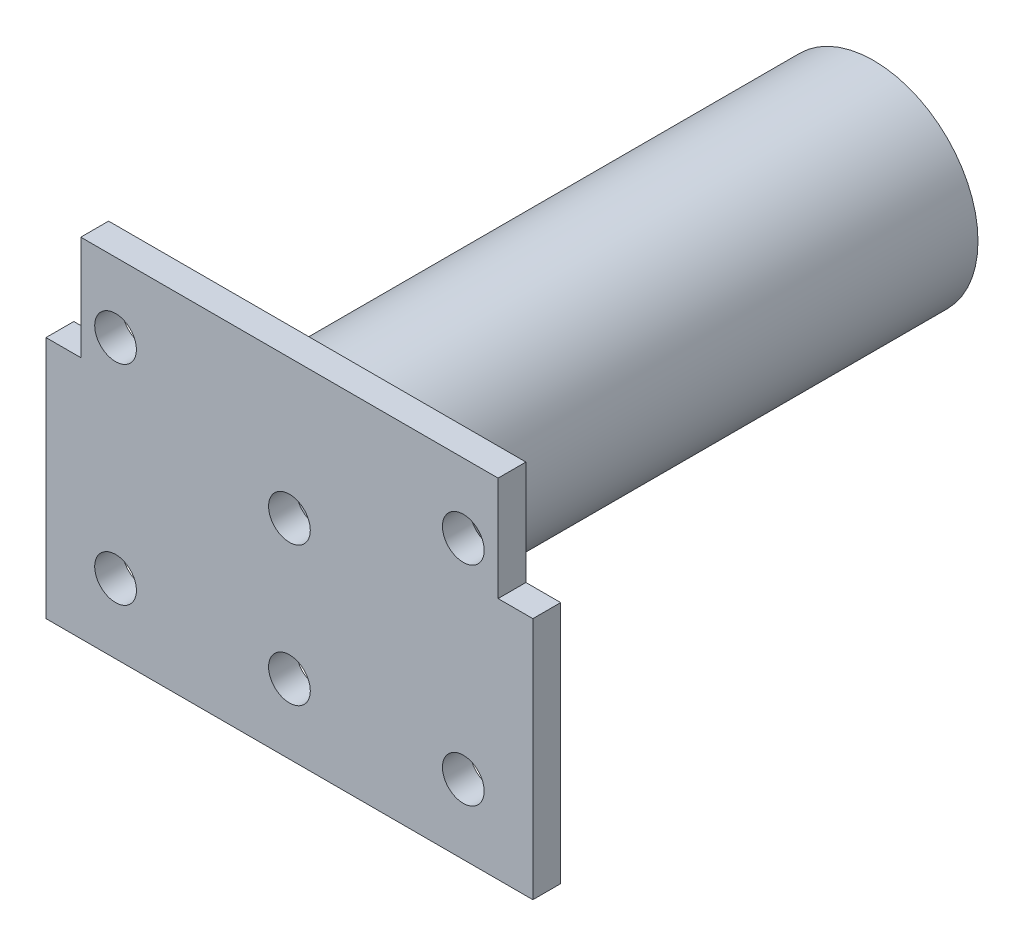
SolidWorks part; units mm, degrees
ref_plane "Alzado" through (0, 0, 0) normal (0, 0, 1) x (1, 0, 0)
ref_plane "Planta" through (0, 0, 0) normal (0, 1, 0) x (1, 0, 0)
ref_plane "Vista lateral" through (0, 0, 0) normal (1, 0, 0) x (0, 0, -1)
sketch "Croquis1" plane through (0, 0, 0) normal (0, 0, 1) x (1, 0, 0)
  line L1 (-35, -15) -> (35, -15)
  line L2 (-35, -15) -> (-35, 15)
  line L3 (-35, 15) -> (35, 15)
  line L4 (35, -15) -> (35, 15)
  circle A3 centre (0, -5) radius 3
  circle A4 centre (25, -5) radius 3
  circle A5 centre (-25, -5) radius 3
  point P0 (0, 0)
  dimension "D3" = 6
  dimension "D4" = 6
  dimension "D5" = 6
  dimension "D7" = 10
  dimension "D6" = 10
  dimension "D8" = 35
  dimension "D1" = 30
  dimension "D2" = 70
extrude "Saliente-Extruir1" add sketch "Croquis1" along normal blind 4
sketch "Croquis3" plane through (0, 0, 0) normal (0, 0, 1) x (1, 0, 0)
  line L0 (35, 15) -> (35, 35)
  line L1 (35, 35) -> (-35, 35)
  line L2 (-35, 35) -> (-35, 15)
  line L3 (35, 15) -> (-35, 15)
  dimension "D1" = 20
extrude "Saliente-Extruir2" add sketch "Croquis3" along normal blind 4
sketch "Croquis4" plane through (0, 0, 0) normal (0, 0, -1) x (-1, 0, 0)
  line L0 (-35, -15) -> (-35, 35) construction
  line L1 (-35, 35) -> (35, 35) construction
  circle A0 centre (0, 15) radius 15
  dimension "D1" = 30
  dimension "D2" = 35
  dimension "D3" = 20
extrude "Saliente-Extruir3" add sketch "Croquis4" along normal blind 80
sketch "Croquis5" plane through (0, 0, 0) normal (0, 0, -1) x (-1, 0, 0)
  line L0 (-35, -15) -> (-35, 35) construction
  line L1 (-35, 35) -> (35, 35) construction
  line L2 (35, 35) -> (35, -15) construction
  circle A0 centre (-25, 25) radius 3
  circle A1 centre (25, 25) radius 3
  dimension "D1" = 6
  dimension "D2" = 6
  dimension "D4" = 10
  dimension "D5" = 10
  dimension "D6" = 10
  dimension "D3" = 10
extrude "Cortar-Extruir1" cut sketch "Croquis5" against normal up to surface (4 mm away) up to face at (0, 10, 4)
sketch "Croquis6" plane through (0, 0, 4) normal (0, 0, 1) x (1, 0, 0)
  line L2 (35, 35) -> (-35, 35) construction
  line L3 (-35, 35) -> (-35, -15) construction
  circle A1 centre (0, 15) radius 3
  dimension "D1" = 20
  dimension "D2" = 35
  dimension "D4" = 6
sketch "Croquis7" plane through (0, 0, -80) normal (0, 0, -1) x (-1, 0, 0)
  circle A0 centre (0, 15) radius 13.5
  dimension "D1" = 27
extrude "Cortar-Extruir2" cut sketch "Croquis7" against normal up to surface (80 mm away) up to face at (22, 25, 0)
extrude "Cortar-Extruir3" cut sketch "Croquis6" against normal up to surface (4 mm away) up to face at (-13.5, 15, 0)
sketch "Croquis8" plane through (0, 0, 0) normal (0, 0, -1) x (-1, 0, 0)
  line L0 (-35, 35) -> (-30, 35)
  line L1 (-35, 35) -> (35, 35) construction
  line L2 (35, 35) -> (30, 35)
  line L3 (-30, 35) -> (-30, 20)
  line L4 (-30, 20) -> (-35, 20)
  line L5 (-35, -15) -> (-35, 35) construction
  line L6 (-35, 20) -> (-35, 35)
  line L7 (30, 35) -> (30, 20)
  line L8 (30, 20) -> (35, 20)
  line L9 (35, 35) -> (35, -15) construction
  line L10 (35, 20) -> (35, 35)
  dimension "D1" = 5
  dimension "D2" = 5
  dimension "D3" = 15
  dimension "D4" = 15
extrude "Cortar-Extruir4" cut sketch "Croquis8" against normal up to surface (4 mm away) up to face at (3, 15, 4)
